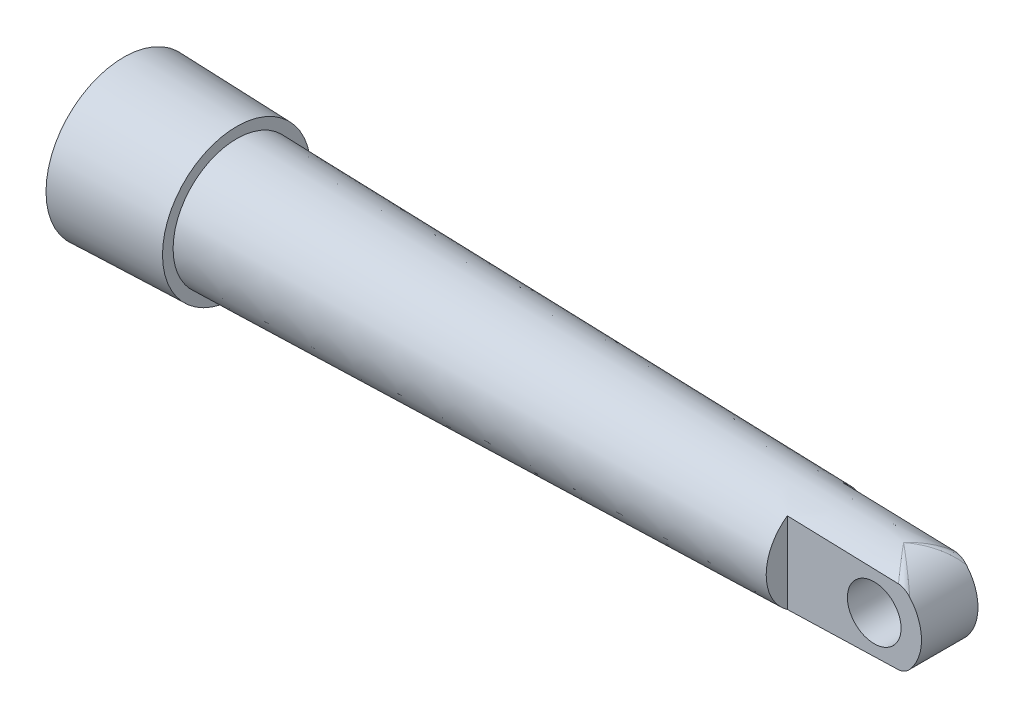
SolidWorks part; units mm, degrees
ref_plane "Front Plane" through (0, 0, 0) normal (0, 0, 1) x (1, 0, 0)
ref_plane "Top Plane" through (0, 0, 0) normal (0, 1, 0) x (1, 0, 0)
ref_plane "Right Plane" through (0, 0, 0) normal (1, 0, 0) x (0, 0, -1)
sketch "Sketch2" plane through (0, 0, 0) normal (0, 0, 1) x (1, 0, 0)
  line L0 (0, 0) -> (0, 2.75)
  line L1 (0, 0) -> (24.5, 0)
  line L2 (24.5, 0) -> (24.5, 1.75)
  line L3 (24.5, 1.75) -> (4, 2.25)
  line L4 (4, 2.25) -> (4, 2.625)
  line L5 (0, 2.75) -> (4, 2.625)
  dimension "D1" = 24.5
  dimension "D2" = 2.75
  dimension "D3" = 1.75
  dimension "D4" = 2.625
  dimension "D5" = 2.25
  dimension "D6" = 4
revolve "Revolve1" add sketch "Sketch2" angle 360 about L1
sketch "Sketch3" plane through (0, 0, 0) normal (0, 0, 1) x (1, 0, 0)
  line L0 (24.5, 1.75) -> (24.5, -1.75)
  line L1 (24.5, -1.75) -> (27.6163, -1.674)
  line L2 (27.6163, 1.674) -> (24.5, 1.75)
  line L3 (24.5, 1.75) -> (4, 2.25) construction
  line L4 (4, -2.25) -> (24.5, -1.75) construction
  arc A0 (27.6163, -1.674) -> (27.6163, 1.674) centre (27.5755, 0) ccw
  point P12 (29.25, 0)
  dimension "D1" = 4.75
extrude "Boss-Extrude1" add sketch "Sketch3" along normal mid plane 2
sketch "Sketch4" plane through (0, 0, 0) normal (0, 0, 1) x (1, 0, 0)
  line L0 (24.5, 1.75) -> (30.0628, 1.6143)
  line L1 (27.6163, 1.674) -> (24.5, 1.75) construction
  line L2 (24.5, 1.75) -> (24.5, 2.5)
  line L3 (24.5, 2.5) -> (30.0628, 2.5)
  line L4 (24.5, 1.4361) -> (24.5, -1.4361) construction
  line L5 (30.0628, 2.5) -> (30.0628, 1.6143)
  line L6 (24.5, 0) -> (25.9297, 0) construction
  point P9 (24.5, 0)
  dimension "D1" = 2.5
revolve "Cut-Revolve1" cut sketch "Sketch4" angle 360 about L6
sketch "Sketch5" plane through (0, 0, 1) normal (0, 0, 1) x (1, 0, 0)
  circle A0 centre (27.5755, 0) radius 0.95
  dimension "D1" = 1.9
extrude "Cut-Extrude1" cut sketch "Sketch5" against normal blind 2
fillet "Fillet1" radius 0.3 4 edges at (28.3737, 1.472, -0.7575) (28.0769, -1.5977, -0.4607) (28.0769, 1.5977, 0.4607) (28.3737, -1.472, 0.7575)
sketch "Sketch6" plane through (0, 0, 0) normal (-1, 0, 0) x (0, 0, 1)
  circle A0 centre (0, 0) radius 1
  dimension "D1" = 2
extrude "Cut-Extrude2" cut sketch "Sketch6" against normal blind 15
